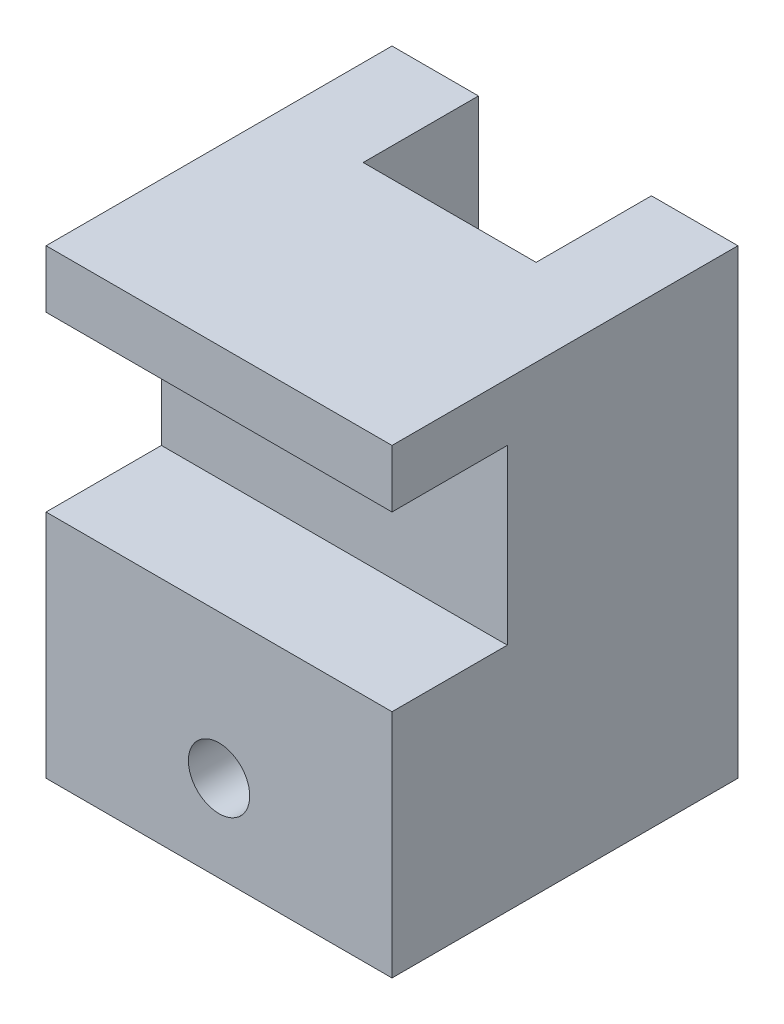
SolidWorks part; units mm, degrees
ref_plane "Front Plane" through (0, 0, 0) normal (0, 0, 1) x (1, 0, 0)
ref_plane "Top Plane" through (0, 0, 0) normal (0, 1, 0) x (1, 0, 0)
ref_plane "Right Plane" through (0, 0, 0) normal (1, 0, 0) x (0, 0, -1)
sketch "Sketch1" plane through (0, 0, 0) normal (0, 0, 1) x (1, 0, 0)
  line L1 (-19.05, -25.4) -> (19.05, -25.4)
  line L2 (-19.05, -25.4) -> (-19.05, 25.4)
  line L3 (-19.05, 25.4) -> (19.05, 25.4)
  line L4 (19.05, -25.4) -> (19.05, 25.4)
  line L5 (-19.05, -25.4) -> (19.05, 25.4) construction
  line L6 (-19.05, 25.4) -> (19.05, -25.4) construction
  point P0 (0, 0)
  dimension "D1" = 38.1
  dimension "D2" = 50.8
extrude "Boss-Extrude1" add sketch "Sketch1" along normal mid plane 38.1 contours L3 L4 L1 L2
sketch "Sketch2" plane through (0, 0, -19.05) normal (0, 0, -1) x (-1, 0, 0)
  line L0 (19.05, 25.4) -> (-19.05, 25.4) construction
  line L1 (-9.525, -25.4) -> (9.525, -25.4)
  line L2 (-9.525, -25.4) -> (-9.525, 25.4)
  line L3 (-9.525, 25.4) -> (9.525, 25.4)
  line L4 (9.525, -25.4) -> (9.525, 25.4)
  line L5 (-9.525, -25.4) -> (9.525, 25.4) construction
  line L6 (-9.525, 25.4) -> (9.525, -25.4) construction
  point P0 (0, 0)
  dimension "D1" = 19.05
extrude "Cut-Extrude1" cut sketch "Sketch2" against normal blind 12.7
sketch "Sketch3" plane through (0, 0, 19.05) normal (0, 0, 1) x (1, 0, 0)
  line L0 (0, -55) -> (0, 55) construction
  line L1 (-19.05, 0) -> (19.05, 0)
  line L2 (-19.05, 0) -> (-19.05, 19.05)
  line L3 (-19.05, 19.05) -> (19.05, 19.05)
  line L4 (19.05, 0) -> (19.05, 19.05)
  line L5 (-19.05, 0) -> (19.05, 19.05) construction
  line L6 (-19.05, 19.05) -> (19.05, 0) construction
  line L7 (19.05, -25.4) -> (19.05, 25.4) construction
  line L8 (-19.05, 25.4) -> (19.05, 25.4) construction
  point P0 (0, 9.525)
  dimension "D1" = 19.05
  dimension "D2" = 15.875
extrude "Cut-Extrude2" cut sketch "Sketch3" against normal blind 12.7
sketch "Sketch4" plane through (0, 0, 19.05) normal (0, 0, 1) x (1, 0, 0)
  line L0 (0, -20.955) -> (0, 20.955) construction
  line L2 (-19.05, -25.4) -> (19.05, -25.4) construction
  circle A0 centre (0, -15.875) radius 14.2875 construction
  point P0 (0, -15.875)
  dimension "D1" = 28.575
  dimension "D2" = 9.525
hole_wizard "1/4 Clearance Hole1" positions "Sketch5" profile "Sketch6" hole size "1/4" standard "ANSI Inch" end condition through all
sketch "Sketch5" plane through (0, 0, 19.05) normal (0, 0, 1) x (1, 0, 0)
  point P0 (0, -15.875)
sketch "Sketch6" plane through (0, -15.875, 19.05) normal (1, 0, 0) x (0, -1, 0)
  line L0 (0, 0) -> (0, 38.1)
  line L1 (0, 38.1) -> (3.3782, 38.1)
  line L2 (3.3782, 38.1) -> (3.3782, 0)
  line L5 (3.3782, 0) -> (0, 0)
  line L11 (0, -6.35) -> (0, 107.95) construction
  dimension "Thru Hole Dia." = 6.7564
  dimension "Thru Hole Depth" = 38.1
sketch "Sketch7" plane through (0, 0, 6.35) normal (0, 0, 1) x (1, 0, 0)
  line L0 (0, -20.955) -> (0, 20.955) construction
  line L1 (19.05, 19.05) -> (-19.05, 19.05) construction
  point P0 (0, 9.525)
  dimension "D1" = 9.525
hole_wizard "#8-32 Tapped Hole1" positions "Sketch8" profile "Sketch9" tap size "#8-32" standard "ANSI Inch"
sketch "Sketch8" plane through (0, 0, 6.35) normal (0, 0, 1) x (1, 0, 0)
  point P0 (0, 9.525)
sketch "Sketch9" plane through (0, 9.525, 6.35) normal (1, 0, 0) x (0, -1, 0)
  line L0 (0, 0) -> (0, 11.7058)
  line L1 (0, 11.7058) -> (1.7272, 10.668)
  line L2 (1.7272, 10.668) -> (1.7272, 0)
  line L5 (1.7272, 0) -> (0, 0)
  line L10 (0, 11.7058) -> (-1.7272, 10.668) construction
  line L11 (0, -6.35) -> (0, 107.95) construction
  dimension "Tap Drill Dia." = 3.4544
  dimension "Tap Drill Depth" = 10.668
  dimension "Drill Angle" = 118
